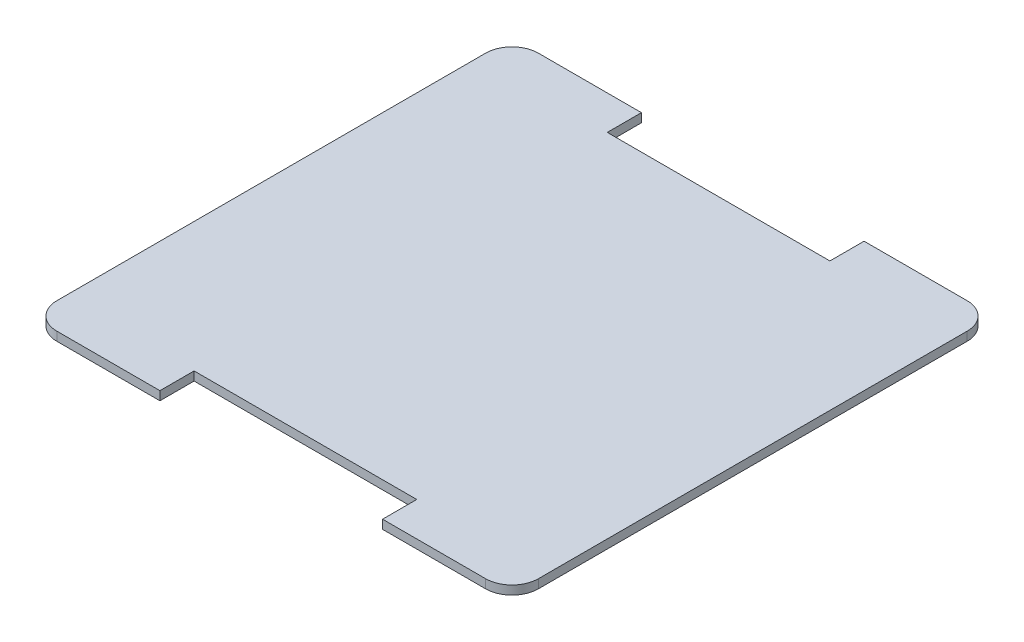
SolidWorks part; units mm, degrees
material "Aleación 1060"
ref_plane "Alzado" through (0, 0, 0) normal (0, 0, 1) x (1, 0, 0)
ref_plane "Planta" through (0, 0, 0) normal (0, 1, 0) x (1, 0, 0)
ref_plane "Vista lateral" through (0, 0, 0) normal (1, 0, 0) x (0, 0, -1)
ref_plane "Plano1" through (0, 54.7071, 0) normal (0, 1, 0) x (1, 0, 0)
sketch "Croquis1" plane through (0, 54.7071, 0) normal (0, 1, 0) x (1, 0, 0)
  line L1 (-52.102, -77.1) -> (-52.102, -452.9) construction
  line L2 (49.153, -77.1) -> (166.8935, -77.1) construction
  line L48 (-153.357, -77.1) -> (-153.357, -40) construction
  line L55 (-153.357, -77.1) -> (49.153, -77.1) construction
  line L63 (49.153, -77.1) -> (49.153, -40) construction
  line L72 (49.153, -452.9) -> (49.153, -490) construction
  line L82 (-153.357, -452.9) -> (49.153, -452.9) construction
  line L93 (-153.357, -452.9) -> (-153.357, -490) construction
  line L105 (-247.102, -46.0045) -> (-153.357, -46.0045) construction
  line L106 (49.153, -46.0045) -> (142.898, -46.0045) construction
  line L107 (166.8935, -70) -> (166.8935, -460) construction
  line L108 (142.898, -483.9955) -> (49.153, -483.9955) construction
  line L109 (-153.357, -483.9955) -> (-247.102, -483.9955) construction
  line L110 (-271.0976, -460) -> (-271.0976, -70) construction
  line L111 (-153.357, -77.1) -> (49.153, -77.1)
  line L112 (49.153, -452.9) -> (49.153, -483.9955)
  line L113 (-153.357, -452.9) -> (49.153, -452.9)
  line L114 (-153.357, -452.9) -> (-153.357, -483.9955)
  line L115 (-153.357, -77.1) -> (-153.357, -46.0045)
  line L116 (49.153, -77.1) -> (49.153, -46.0045)
  line L117 (-247.102, -46.0045) -> (-153.357, -46.0045)
  line L118 (49.153, -46.0045) -> (142.898, -46.0045)
  line L119 (166.8935, -70) -> (166.8935, -460)
  line L120 (142.898, -483.9955) -> (49.153, -483.9955)
  line L121 (-153.357, -483.9955) -> (-247.102, -483.9955)
  line L122 (-271.0976, -460) -> (-271.0976, -70)
  circle A0 centre (-181.0976, -265) radius 80
  circle A4 centre (76.8935, -265) radius 80
  arc A56 (-247.102, -46.0045) -> (-271.0976, -70) centre (-247.102, -70) ccw construction
  arc A57 (166.8935, -70) -> (142.898, -46.0045) centre (142.898, -70) ccw construction
  arc A58 (142.898, -483.9955) -> (166.8935, -460) centre (142.898, -460) ccw construction
  arc A59 (-271.0976, -460) -> (-247.102, -483.9955) centre (-247.102, -460) ccw construction
  arc A60 (-247.102, -46.0045) -> (-271.0976, -70) centre (-247.102, -70) ccw
  arc A61 (166.8935, -70) -> (142.898, -46.0045) centre (142.898, -70) ccw
  arc A62 (142.898, -483.9955) -> (166.8935, -460) centre (142.898, -460) ccw
  arc A63 (-271.0976, -460) -> (-247.102, -483.9955) centre (-247.102, -460) ccw
  point P0 (156.8935, -265)
  point P10 (-52.102, -265)
  point P11 (76.8935, -185)
  dimension "D1" = 160
  dimension "D2" = 10
extrude "Saliente-Extruir1" add sketch "Croquis1" along normal mid plane 8 contours L113 L112 L120 A62 L119 A61 L118 L116 L111 L115 L117 A60 L122 A63 L121 L114
sketch "Croquis2" plane through (0, 58.7071, 0) normal (0, 1, 0) x (1, 0, 0)
  line L0 (-52.102, -77.1) -> (-52.102, -452.9) construction
  line L1 (26.8935, -155) -> (126.8935, -155) construction
  line L2 (26.8935, -155) -> (26.8935, -375) construction
  line L3 (26.8935, -375) -> (126.8935, -375) construction
  line L4 (126.8935, -155) -> (126.8935, -375) construction
  line L5 (49.153, -77.1) -> (-153.357, -77.1) construction
  line L6 (-153.357, -452.9) -> (49.153, -452.9) construction
  line L7 (-231.0976, -155) -> (-231.0976, -375) construction
  line L8 (-131.0976, -375) -> (-231.0976, -375) construction
  line L9 (-131.0976, -155) -> (-131.0976, -375) construction
  line L10 (-131.0976, -155) -> (-231.0976, -155) construction
  line L11 (-271.0976, -265) -> (166.8935, -265) construction
  line L12 (-112.102, -77.1) -> (7.898, -77.1) construction
  line L13 (-112.102, -77.1) -> (-112.102, -229.5) construction
  line L14 (-112.102, -229.5) -> (7.898, -229.5) construction
  line L15 (7.898, -77.1) -> (7.898, -229.5) construction
  line L16 (-271.0976, -70) -> (-271.0976, -460) construction
  line L17 (166.8935, -460) -> (166.8935, -70) construction
  line L18 (-112.102, -300.5) -> (7.898, -300.5) construction
  line L19 (7.898, -452.9) -> (7.898, -300.5) construction
  line L20 (-112.102, -452.9) -> (7.898, -452.9) construction
  line L21 (-112.102, -452.9) -> (-112.102, -300.5) construction
  line L22 (-131.0976, -155) -> (-231.0976, -155) construction
  line L23 (-131.0976, -375) -> (-131.0976, -155) construction
  line L24 (-231.0976, -375) -> (-231.0976, -155) construction
  line L25 (-131.0976, -375) -> (-231.0976, -375) construction
  line L26 (126.8935, -375) -> (126.8935, -155) construction
  line L27 (26.8935, -155) -> (126.8935, -155) construction
  line L28 (26.8935, -375) -> (26.8935, -155) construction
  line L29 (26.8935, -375) -> (126.8935, -375) construction
  point P4 (76.8935, -265)
  point P7 (76.8935, -155)
  point P8 (26.8935, -265)
  point P18 (-181.0976, -265)
  point P23 (-52.102, -77.1)
  point P42 (76.8935, -265)
  dimension "D1" = 100
  dimension "D2" = 220
  dimension "D3" = 152.4
  dimension "D4" = 120
